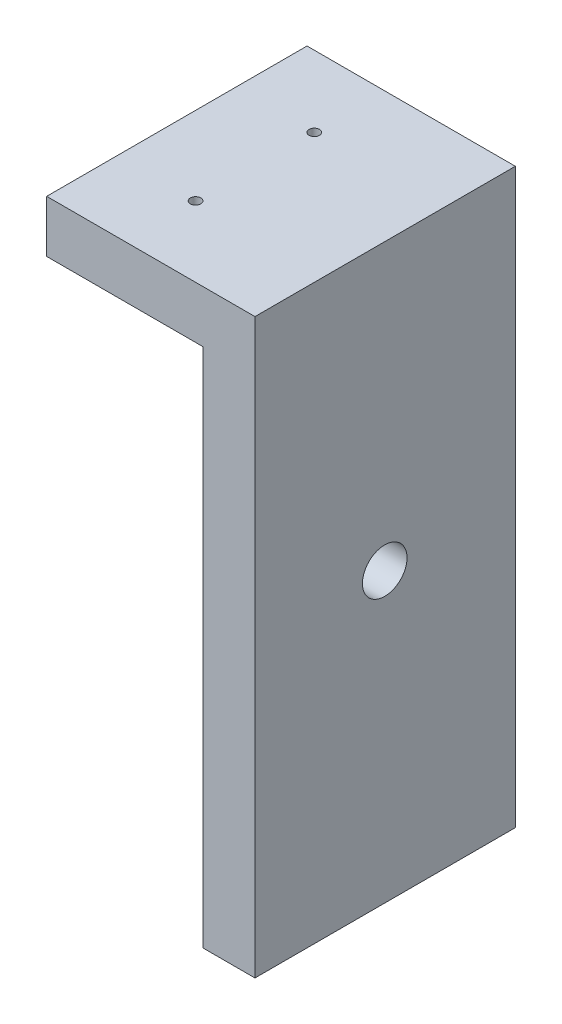
SolidWorks part; units mm, degrees
ref_plane "Front Plane" through (0, 0, 0) normal (0, 0, 1) x (1, 0, 0)
ref_plane "Top Plane" through (0, 0, 0) normal (0, 1, 0) x (1, 0, 0)
ref_plane "Right Plane" through (0, 0, 0) normal (1, 0, 0) x (0, 0, -1)
sketch "Sketch1" plane through (0, 0, 0) normal (0, 0, 1) x (1, 0, 0)
  line L1 (0, 0) -> (1, 0)
  line L2 (0, 0) -> (0, 10)
  line L3 (0, 10) -> (1, 10)
  line L4 (1, 0) -> (1, 10)
extrude "Boss-Extrude1" add sketch "Sketch1" along normal blind 5
sketch "Sketch2" plane through (0, 10, 0) normal (0, 1, 0) x (1, 0, 0)
  line L1 (1, 0) -> (-3, 0)
  line L2 (1, 0) -> (1, -5)
  line L3 (1, -5) -> (-3, -5)
  line L4 (-3, 0) -> (-3, -5)
extrude "Boss-Extrude2" add sketch "Sketch2" along normal blind 1
sketch "Sketch3" plane through (1, 0, 0) normal (1, 0, 0) x (0, 0, -1)
  circle A0 centre (-2.508, 5.529) radius 0.4282
  point P2 (0, 0)
extrude "Cut-Extrude1" cut sketch "Sketch3" against normal blind 1
sketch "Sketch4" plane through (0, 10, 0) normal (0, -1, 0) x (-1, 0, 0)
  circle A0 centre (1.4941, -1.3668) radius 0.1
  circle A1 centre (1.4941, -3.6463) radius 0.1
extrude "Cut-Extrude2" cut sketch "Sketch4" against normal blind 1
